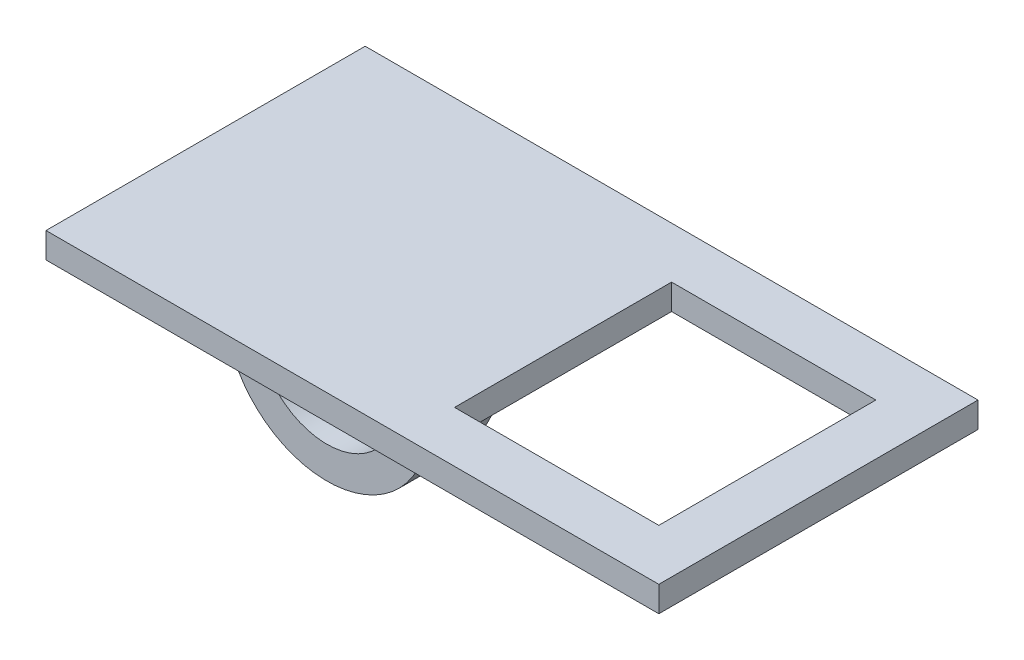
SolidWorks part; units mm, degrees
ref_plane "Front" through (0, 0, 0) normal (0, 0, 1) x (1, 0, 0)
ref_plane "Top" through (0, 0, 0) normal (0, 1, 0) x (1, 0, 0)
ref_plane "Right" through (0, 0, 0) normal (1, 0, 0) x (0, 0, -1)
sketch "Эскиз1" plane through (0, 0, 0) normal (0, 1, 0) x (1, 0, 0)
  line L1 (-24, 12.5) -> (24, 12.5)
  line L2 (-24, 12.5) -> (-24, -12.5)
  line L3 (-24, -12.5) -> (24, -12.5)
  line L4 (24, 12.5) -> (24, -12.5)
  line L5 (-24, 12.5) -> (24, -12.5) construction
  line L6 (-24, -12.5) -> (24, 12.5) construction
  point P0 (0, 0)
  dimension "D1" = 48
  dimension "D2" = 25
extrude "Бобышка-Вытянуть1" add sketch "Эскиз1" along normal blind 2
sketch "Эскиз2" plane through (0, 0, 0) normal (0, 0, 1) x (1, 0, 0)
  line L0 (0, 2) -> (0, -16.4079) construction
  line L1 (-24, 0) -> (-23.4837, -5.337)
  line L2 (-24, 0) -> (24, 0) construction
  line L3 (0, 0) -> (-4.8612, -9.6108)
  line L4 (-24, 0) -> (0, 0)
  line L5 (-24, 2) -> (24, 2) construction
  line L6 (-12, -6) -> (-12, 9.2672) construction
  circle A0 centre (-12, -6) radius 5.5
  circle A2 centre (-20, -5) radius 1.5
  circle A3 centre (-20, -5) radius 3.5
  arc A4 (-17.2915, 0) -> (-6.7085, 0) centre (-12, -6) ccw
  dimension "D1" = 11
  dimension "D5" = 3
  dimension "D6" = 7
  dimension "D10" = 16
  dimension "D3" = 6
  dimension "D7" = 12
  dimension "D8" = 5
  dimension "D9" = 8
extrude "Бобышка-Вытянуть2" add sketch "Эскиз2" along normal mid plane 5 separate body contours A4 L4 L1 A3 | A4 L3 L4 | A4 A3 A2 | A3 A4 A2 A0 | L4 A4 A3 A0
sketch "Эскиз6" plane through (0, 0, 0) normal (0, -1, 0) x (1, 0, 0)
  line L0 (-24, 12.5) -> (24, 12.5) construction
  line L1 (4, 8.5) -> (20, 8.5)
  line L2 (4, 8.5) -> (4, -8.5)
  line L3 (4, -8.5) -> (20, -8.5)
  line L4 (20, 8.5) -> (20, -8.5)
  line L5 (24, 12.5) -> (24, -12.5) construction
  line L6 (24, -12.5) -> (-24, -12.5) construction
  line L7 (0, 2.5) -> (0, -2.5) construction
  dimension "D1" = 4
  dimension "D2" = 4
  dimension "D3" = 4
  dimension "D4" = 4
extrude "Вырез-Вытянуть3" cut sketch "Эскиз6" against normal blind 4
